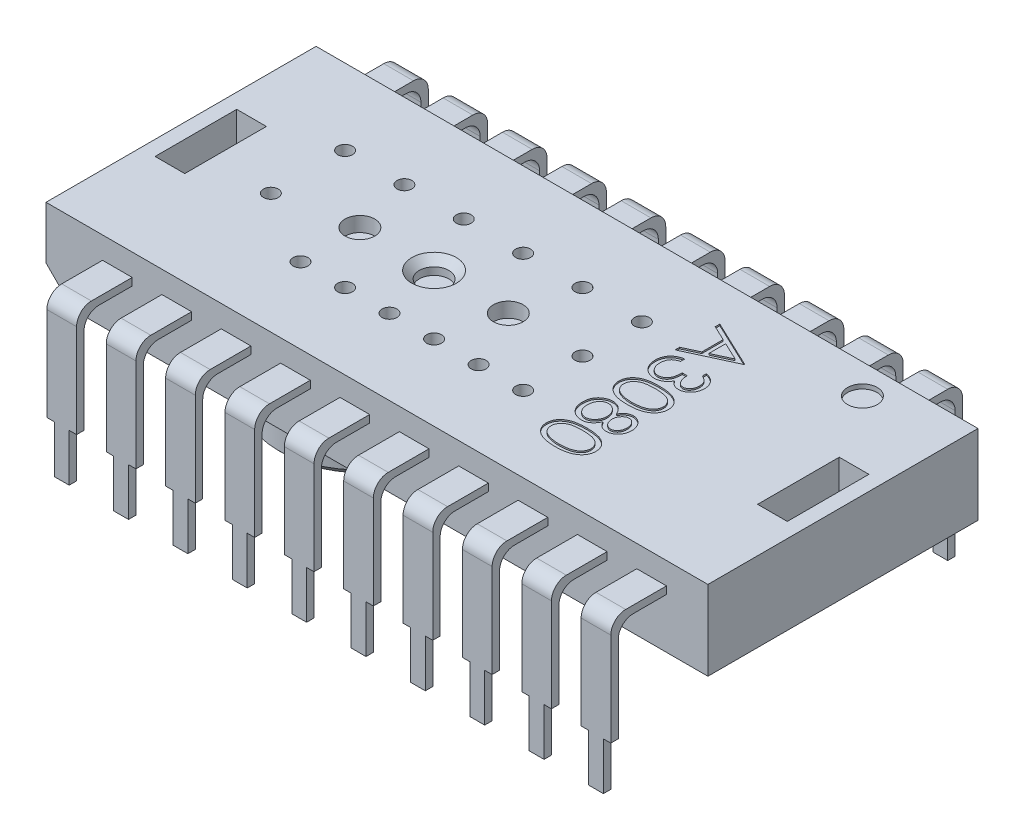
SolidWorks part; units mm, degrees
ref_plane "Front Plane" through (0, 0, 0) normal (0, 0, 1) x (1, 0, 0)
ref_plane "Top Plane" through (0, 0, 0) normal (0, 1, 0) x (1, 0, 0)
ref_plane "Right Plane" through (0, 0, 0) normal (1, 0, 0) x (0, 0, -1)
sketch "Sketch1" plane through (0, 0, 0) normal (0, 1, 0) x (1, 0, 0)
  line L1 (0, 0) -> (22.3, 0)
  line L2 (0, 0) -> (0, 9.1)
  line L3 (0, 9.1) -> (22.3, 9.1)
  line L4 (22.3, 0) -> (22.3, 9.1)
  dimension "D1" = 22.3
  dimension "D2" = 9.1
extrude "Boss-Extrude1" add sketch "Sketch1" along normal blind 3.18
sketch "Sketch2" plane through (0, 0, 0) normal (0, -1, 0) x (-1, 0, 0)
  line L0 (0, 4.55) -> (-22.3, 4.55) construction
  line L1 (0, 9.1) -> (0, 0) construction
  line L2 (-22.3, 0) -> (-22.3, 9.1) construction
  circle A0 centre (-6.025, 4.55) radius 2.8
  circle A1 centre (-6.025, 4.55) radius 0.525
  dimension "D1" = 5.6
  dimension "D3" = 1.05
  dimension "D2" = 6.025
extrude "Boss-Extrude2" add sketch "Sketch2" along normal blind 2.25 draft 1.5
chamfer "Chamfer1" distance 0.3 angle 45 1 edges at (6.025, -2.25, -7.2911)
ref_plane "Plane1" through (0, 2.19, 0) normal (0, 1, 0) x (1, 0, 0)
sketch "Sketch3" plane through (0, 2.19, 0) normal (0, 1, 0) x (1, 0, 0)
  line L0 (18.905, 9.1) -> (18.905, 10.975)
  line L1 (22.3, 9.1) -> (0, 9.1) construction
  line L2 (18.905, 10.975) -> (19.905, 10.975)
  line L3 (19.905, 10.975) -> (19.905, 9.1)
  line L4 (16.905, 9.1) -> (16.905, 10.975)
  line L5 (16.905, 10.975) -> (17.905, 10.975)
  line L6 (17.905, 10.975) -> (17.905, 9.1)
  line L7 (14.905, 9.1) -> (14.905, 10.975)
  line L8 (14.905, 10.975) -> (15.905, 10.975)
  line L9 (15.905, 10.975) -> (15.905, 9.1)
  line L10 (12.905, 9.1) -> (12.905, 10.975)
  line L11 (12.905, 10.975) -> (13.905, 10.975)
  line L12 (13.905, 10.975) -> (13.905, 9.1)
  line L13 (10.905, 9.1) -> (10.905, 10.975)
  line L14 (10.905, 10.975) -> (11.905, 10.975)
  line L15 (11.905, 10.975) -> (11.905, 9.1)
  line L16 (8.905, 9.1) -> (8.905, 10.975)
  line L17 (8.905, 10.975) -> (9.905, 10.975)
  line L18 (9.905, 10.975) -> (9.905, 9.1)
  line L19 (6.905, 9.1) -> (6.905, 10.975)
  line L20 (6.905, 10.975) -> (7.905, 10.975)
  line L21 (7.905, 10.975) -> (7.905, 9.1)
  line L22 (4.905, 9.1) -> (4.905, 10.975)
  line L23 (4.905, 10.975) -> (5.905, 10.975)
  line L24 (5.905, 10.975) -> (5.905, 9.1)
  line L25 (2.905, 9.1) -> (2.905, 10.975)
  line L26 (2.905, 10.975) -> (3.905, 10.975)
  line L27 (3.905, 10.975) -> (3.905, 9.1)
  line L28 (0.905, 9.1) -> (0.905, 10.975)
  line L29 (0.905, 10.975) -> (1.905, 10.975)
  line L30 (1.905, 10.975) -> (1.905, 9.1)
  line L31 (0, 0) -> (22.3, 0) construction
  line L32 (20.905, 0) -> (19.905, 0)
  line L33 (20.905, 0) -> (20.905, -1.875)
  line L34 (20.905, -1.875) -> (19.905, -1.875)
  line L35 (19.905, 0) -> (19.905, -1.875)
  line L36 (18.905, 0) -> (17.905, 0)
  line L37 (18.905, 0) -> (18.905, -1.875)
  line L38 (18.905, -1.875) -> (17.905, -1.875)
  line L39 (17.905, 0) -> (17.905, -1.875)
  line L40 (16.905, 0) -> (15.905, 0)
  line L41 (16.905, 0) -> (16.905, -1.875)
  line L42 (16.905, -1.875) -> (15.905, -1.875)
  line L43 (15.905, 0) -> (15.905, -1.875)
  line L44 (14.905, 0) -> (13.905, 0)
  line L45 (14.905, 0) -> (14.905, -1.875)
  line L46 (14.905, -1.875) -> (13.905, -1.875)
  line L47 (13.905, 0) -> (13.905, -1.875)
  line L48 (12.905, 0) -> (11.905, 0)
  line L49 (12.905, 0) -> (12.905, -1.875)
  line L50 (12.905, -1.875) -> (11.905, -1.875)
  line L51 (11.905, 0) -> (11.905, -1.875)
  line L52 (10.905, 0) -> (9.905, 0)
  line L53 (10.905, 0) -> (10.905, -1.875)
  line L54 (10.905, -1.875) -> (9.905, -1.875)
  line L55 (9.905, 0) -> (9.905, -1.875)
  line L56 (8.905, 0) -> (7.905, 0)
  line L57 (8.905, 0) -> (8.905, -1.875)
  line L58 (8.905, -1.875) -> (7.905, -1.875)
  line L59 (7.905, 0) -> (7.905, -1.875)
  line L60 (6.905, 0) -> (5.905, 0)
  line L61 (6.905, 0) -> (6.905, -1.875)
  line L62 (6.905, -1.875) -> (5.905, -1.875)
  line L63 (5.905, 0) -> (5.905, -1.875)
  line L64 (4.905, 0) -> (3.905, 0)
  line L65 (4.905, 0) -> (4.905, -1.875)
  line L66 (4.905, -1.875) -> (3.905, -1.875)
  line L67 (3.905, 0) -> (3.905, -1.875)
  line L68 (2.905, 0) -> (1.905, 0)
  line L69 (2.905, 0) -> (2.905, -1.875)
  line L70 (2.905, -1.875) -> (1.905, -1.875)
  line L71 (1.905, 0) -> (1.905, -1.875)
  line L72 (19.905, 9.1) -> (18.905, 9.1)
  line L73 (17.905, 9.1) -> (16.905, 9.1)
  line L74 (1.905, 9.1) -> (0.905, 9.1)
  line L75 (3.905, 9.1) -> (2.905, 9.1)
  line L76 (5.905, 9.1) -> (4.905, 9.1)
  line L77 (7.905, 9.1) -> (6.905, 9.1)
  line L78 (9.905, 9.1) -> (8.905, 9.1)
  line L79 (11.905, 9.1) -> (10.905, 9.1)
  line L80 (13.905, 9.1) -> (12.905, 9.1)
  line L81 (15.905, 9.1) -> (14.905, 9.1)
  circle A0 centre (6.025, 4.55) radius 0.525 construction
  point P6 (19.405, 10.975)
  point P51 (20.405, 0)
  dimension "D1" = 1.875
  dimension "D2" = 1
  dimension "D3" = 13.38
  dimension "D5" = 1.875
  dimension "D6" = 1
  dimension "D7" = 1
  dimension "D4" = 10
  dimension "D8" = 10
extrude "Boss-Extrude3" add sketch "Sketch3" along normal blind 0.25
sketch "Sketch5" plane through (0, 0, 1.875) normal (0, 0, 1) x (1, 0, 0)
  line L0 (2.905, 2.44) -> (1.905, 2.44) construction
  line L1 (1.905, 2.19) -> (2.905, 2.19)
  line L2 (1.905, 2.19) -> (1.905, -1.21)
  line L3 (2.155, -4.61) -> (2.655, -4.61)
  line L4 (2.905, 2.19) -> (2.905, -1.21)
  line L5 (1.905, -1.21) -> (2.155, -1.21)
  line L6 (0, 0) -> (22.3, 0) construction
  line L7 (2.405, 2.19) -> (2.405, -4.61) construction
  line L8 (2.155, -1.21) -> (2.155, -4.61)
  line L9 (2.655, -1.21) -> (2.655, -4.61)
  line L10 (2.655, -1.21) -> (2.905, -1.21)
  line L11 (3.905, 2.19) -> (4.905, 2.19)
  line L12 (3.905, 2.19) -> (3.905, -1.21)
  line L13 (4.155, -4.61) -> (4.655, -4.61)
  line L14 (4.905, 2.19) -> (4.905, -1.21)
  line L15 (3.905, -1.21) -> (4.155, -1.21)
  line L16 (4.155, -1.21) -> (4.155, -4.61)
  line L17 (4.655, -1.21) -> (4.655, -4.61)
  line L18 (4.655, -1.21) -> (4.905, -1.21)
  line L19 (4.405, 2.19) -> (4.405, -4.61) construction
  line L20 (5.905, 2.19) -> (6.905, 2.19)
  line L21 (5.905, 2.19) -> (5.905, -1.21)
  line L22 (6.155, -4.61) -> (6.655, -4.61)
  line L23 (6.905, 2.19) -> (6.905, -1.21)
  line L24 (5.905, -1.21) -> (6.155, -1.21)
  line L25 (6.155, -1.21) -> (6.155, -4.61)
  line L26 (6.655, -1.21) -> (6.655, -4.61)
  line L27 (6.655, -1.21) -> (6.905, -1.21)
  line L28 (6.405, 2.19) -> (6.405, -4.61) construction
  line L29 (7.905, 2.19) -> (8.905, 2.19)
  line L30 (7.905, 2.19) -> (7.905, -1.21)
  line L31 (8.155, -4.61) -> (8.655, -4.61)
  line L32 (8.905, 2.19) -> (8.905, -1.21)
  line L33 (7.905, -1.21) -> (8.155, -1.21)
  line L34 (8.155, -1.21) -> (8.155, -4.61)
  line L35 (8.655, -1.21) -> (8.655, -4.61)
  line L36 (8.655, -1.21) -> (8.905, -1.21)
  line L37 (8.405, 2.19) -> (8.405, -4.61) construction
  line L38 (9.905, 2.19) -> (10.905, 2.19)
  line L39 (9.905, 2.19) -> (9.905, -1.21)
  line L40 (10.155, -4.61) -> (10.655, -4.61)
  line L41 (10.905, 2.19) -> (10.905, -1.21)
  line L42 (9.905, -1.21) -> (10.155, -1.21)
  line L43 (10.155, -1.21) -> (10.155, -4.61)
  line L44 (10.655, -1.21) -> (10.655, -4.61)
  line L45 (10.655, -1.21) -> (10.905, -1.21)
  line L46 (10.405, 2.19) -> (10.405, -4.61) construction
  line L47 (11.905, 2.19) -> (12.905, 2.19)
  line L48 (11.905, 2.19) -> (11.905, -1.21)
  line L49 (12.155, -4.61) -> (12.655, -4.61)
  line L50 (12.905, 2.19) -> (12.905, -1.21)
  line L51 (11.905, -1.21) -> (12.155, -1.21)
  line L52 (12.155, -1.21) -> (12.155, -4.61)
  line L53 (12.655, -1.21) -> (12.655, -4.61)
  line L54 (12.655, -1.21) -> (12.905, -1.21)
  line L55 (12.405, 2.19) -> (12.405, -4.61) construction
  line L56 (13.905, 2.19) -> (14.905, 2.19)
  line L57 (13.905, 2.19) -> (13.905, -1.21)
  line L58 (14.155, -4.61) -> (14.655, -4.61)
  line L59 (14.905, 2.19) -> (14.905, -1.21)
  line L60 (13.905, -1.21) -> (14.155, -1.21)
  line L61 (14.155, -1.21) -> (14.155, -4.61)
  line L62 (14.655, -1.21) -> (14.655, -4.61)
  line L63 (14.655, -1.21) -> (14.905, -1.21)
  line L64 (14.405, 2.19) -> (14.405, -4.61) construction
  line L65 (15.905, 2.19) -> (16.905, 2.19)
  line L66 (15.905, 2.19) -> (15.905, -1.21)
  line L67 (16.155, -4.61) -> (16.655, -4.61)
  line L68 (16.905, 2.19) -> (16.905, -1.21)
  line L69 (15.905, -1.21) -> (16.155, -1.21)
  line L70 (16.155, -1.21) -> (16.155, -4.61)
  line L71 (16.655, -1.21) -> (16.655, -4.61)
  line L72 (16.655, -1.21) -> (16.905, -1.21)
  line L73 (16.405, 2.19) -> (16.405, -4.61) construction
  line L74 (17.905, 2.19) -> (18.905, 2.19)
  line L75 (17.905, 2.19) -> (17.905, -1.21)
  line L76 (18.155, -4.61) -> (18.655, -4.61)
  line L77 (18.905, 2.19) -> (18.905, -1.21)
  line L78 (17.905, -1.21) -> (18.155, -1.21)
  line L79 (18.155, -1.21) -> (18.155, -4.61)
  line L80 (18.655, -1.21) -> (18.655, -4.61)
  line L81 (18.655, -1.21) -> (18.905, -1.21)
  line L82 (18.405, 2.19) -> (18.405, -4.61) construction
  line L83 (19.905, 2.19) -> (20.905, 2.19)
  line L84 (19.905, 2.19) -> (19.905, -1.21)
  line L85 (20.155, -4.61) -> (20.655, -4.61)
  line L86 (20.905, 2.19) -> (20.905, -1.21)
  line L87 (19.905, -1.21) -> (20.155, -1.21)
  line L88 (20.155, -1.21) -> (20.155, -4.61)
  line L89 (20.655, -1.21) -> (20.655, -4.61)
  line L90 (20.655, -1.21) -> (20.905, -1.21)
  line L91 (20.405, 2.19) -> (20.405, -4.61) construction
  dimension "D1" = 1
  dimension "D2" = 7.05
  dimension "D3" = 1.21
  dimension "D4" = 0.25
  dimension "D5" = 0.25
  dimension "D6" = 10
extrude "Boss-Extrude4" add sketch "Sketch5" against normal blind 0.25
sketch "Sketch6" plane through (0, 0, -10.975) normal (0, 0, -1) x (-1, 0, 0)
  line L0 (-19.905, 2.19) -> (-19.905, -1.21)
  line L1 (-19.905, -1.21) -> (-19.655, -1.21)
  line L2 (-19.655, -1.21) -> (-19.655, -4.61)
  line L3 (-19.655, -4.61) -> (-19.155, -4.61)
  line L4 (-19.155, -4.61) -> (-19.155, -1.21)
  line L5 (-19.155, -1.21) -> (-18.905, -1.21)
  line L6 (-18.905, -1.21) -> (-18.905, 2.19)
  line L7 (-19.905, 2.44) -> (-18.905, 2.44) construction
  line L8 (-19.905, 2.19) -> (-18.905, 2.19)
  line L9 (-17.905, 2.19) -> (-17.905, -1.21)
  line L10 (-17.905, -1.21) -> (-17.655, -1.21)
  line L11 (-17.655, -1.21) -> (-17.655, -4.61)
  line L12 (-17.655, -4.61) -> (-17.155, -4.61)
  line L13 (-17.155, -4.61) -> (-17.155, -1.21)
  line L14 (-17.155, -1.21) -> (-16.905, -1.21)
  line L15 (-16.905, -1.21) -> (-16.905, 2.19)
  line L16 (-17.905, 2.19) -> (-16.905, 2.19)
  line L17 (-15.905, 2.19) -> (-15.905, -1.21)
  line L18 (-15.905, -1.21) -> (-15.655, -1.21)
  line L19 (-15.655, -1.21) -> (-15.655, -4.61)
  line L20 (-15.655, -4.61) -> (-15.155, -4.61)
  line L21 (-15.155, -4.61) -> (-15.155, -1.21)
  line L22 (-15.155, -1.21) -> (-14.905, -1.21)
  line L23 (-14.905, -1.21) -> (-14.905, 2.19)
  line L24 (-15.905, 2.19) -> (-14.905, 2.19)
  line L25 (-13.905, 2.19) -> (-13.905, -1.21)
  line L26 (-13.905, -1.21) -> (-13.655, -1.21)
  line L27 (-13.655, -1.21) -> (-13.655, -4.61)
  line L28 (-13.655, -4.61) -> (-13.155, -4.61)
  line L29 (-13.155, -4.61) -> (-13.155, -1.21)
  line L30 (-13.155, -1.21) -> (-12.905, -1.21)
  line L31 (-12.905, -1.21) -> (-12.905, 2.19)
  line L32 (-13.905, 2.19) -> (-12.905, 2.19)
  line L33 (-11.905, 2.19) -> (-11.905, -1.21)
  line L34 (-11.905, -1.21) -> (-11.655, -1.21)
  line L35 (-11.655, -1.21) -> (-11.655, -4.61)
  line L36 (-11.655, -4.61) -> (-11.155, -4.61)
  line L37 (-11.155, -4.61) -> (-11.155, -1.21)
  line L38 (-11.155, -1.21) -> (-10.905, -1.21)
  line L39 (-10.905, -1.21) -> (-10.905, 2.19)
  line L40 (-11.905, 2.19) -> (-10.905, 2.19)
  line L41 (-9.905, 2.19) -> (-9.905, -1.21)
  line L42 (-9.905, -1.21) -> (-9.655, -1.21)
  line L43 (-9.655, -1.21) -> (-9.655, -4.61)
  line L44 (-9.655, -4.61) -> (-9.155, -4.61)
  line L45 (-9.155, -4.61) -> (-9.155, -1.21)
  line L46 (-9.155, -1.21) -> (-8.905, -1.21)
  line L47 (-8.905, -1.21) -> (-8.905, 2.19)
  line L48 (-9.905, 2.19) -> (-8.905, 2.19)
  line L49 (-7.905, 2.19) -> (-7.905, -1.21)
  line L50 (-7.905, -1.21) -> (-7.655, -1.21)
  line L51 (-7.655, -1.21) -> (-7.655, -4.61)
  line L52 (-7.655, -4.61) -> (-7.155, -4.61)
  line L53 (-7.155, -4.61) -> (-7.155, -1.21)
  line L54 (-7.155, -1.21) -> (-6.905, -1.21)
  line L55 (-6.905, -1.21) -> (-6.905, 2.19)
  line L56 (-7.905, 2.19) -> (-6.905, 2.19)
  line L57 (-5.905, 2.19) -> (-5.905, -1.21)
  line L58 (-5.905, -1.21) -> (-5.655, -1.21)
  line L59 (-5.655, -1.21) -> (-5.655, -4.61)
  line L60 (-5.655, -4.61) -> (-5.155, -4.61)
  line L61 (-5.155, -4.61) -> (-5.155, -1.21)
  line L62 (-5.155, -1.21) -> (-4.905, -1.21)
  line L63 (-4.905, -1.21) -> (-4.905, 2.19)
  line L64 (-5.905, 2.19) -> (-4.905, 2.19)
  line L65 (-3.905, 2.19) -> (-3.905, -1.21)
  line L66 (-3.905, -1.21) -> (-3.655, -1.21)
  line L67 (-3.655, -1.21) -> (-3.655, -4.61)
  line L68 (-3.655, -4.61) -> (-3.155, -4.61)
  line L69 (-3.155, -4.61) -> (-3.155, -1.21)
  line L70 (-3.155, -1.21) -> (-2.905, -1.21)
  line L71 (-2.905, -1.21) -> (-2.905, 2.19)
  line L72 (-3.905, 2.19) -> (-2.905, 2.19)
  line L73 (-1.905, 2.19) -> (-1.905, -1.21)
  line L74 (-1.905, -1.21) -> (-1.655, -1.21)
  line L75 (-1.655, -1.21) -> (-1.655, -4.61)
  line L76 (-1.655, -4.61) -> (-1.155, -4.61)
  line L77 (-1.155, -4.61) -> (-1.155, -1.21)
  line L78 (-1.155, -1.21) -> (-0.905, -1.21)
  line L79 (-0.905, -1.21) -> (-0.905, 2.19)
  line L80 (-1.905, 2.19) -> (-0.905, 2.19)
  dimension "D1" = 3.4
  dimension "D2" = 3.4
  dimension "D3" = 7.05
  dimension "D4" = 0.25
  dimension "D5" = 0.25
  dimension "D6" = 10
extrude "Boss-Extrude5" add sketch "Sketch6" against normal blind 0.25
fillet "Fillet1" radius 0.5 40 edges at (19.405, 2.19, -10.725) (17.405, 2.19, -10.725) (15.405, 2.19, -10.725) (13.405, 2.19, -10.725) (11.405, 2.19, -10.725) (9.405, 2.19, -10.725) (7.405, 2.19, -10.725) (5.405, 2.19, -10.725) (3.405, 2.19, -10.725) (1.405, 2.19, -10.725) (18.405, 2.19, 1.625) (16.405, 2.19, 1.625) (14.405, 2.19, 1.625) (12.405, 2.19, 1.625) (10.405, 2.19, 1.625) (8.405, 2.19, 1.625) (6.405, 2.19, 1.625) (4.405, 2.19, 1.625) (2.405, 2.19, 1.625) (5.405, 2.44, -10.975) (3.405, 2.44, -10.975) (1.405, 2.44, -10.975) (7.405, 2.44, -10.975) (9.405, 2.44, -10.975) (11.405, 2.44, -10.975) (13.405, 2.44, -10.975) (15.405, 2.44, -10.975) (17.405, 2.44, -10.975) (19.405, 2.44, -10.975) (18.405, 2.44, 1.875) (16.405, 2.44, 1.875) (14.405, 2.44, 1.875) (12.405, 2.44, 1.875) (10.405, 2.44, 1.875) (8.405, 2.44, 1.875) (6.405, 2.44, 1.875) (4.405, 2.44, 1.875) (2.405, 2.44, 1.875) (20.405, 2.19, 1.625) (20.405, 2.44, 1.875)
sketch "Sketch7" plane through (0, 0, -10.975) normal (0, 0, 1) x (1, 0, 0)
  line L0 (1.53, -4.61) -> (1.655, -3.61)
  line L1 (1.655, -4.61) -> (1.155, -4.61) construction
  line L2 (1.655, -1.21) -> (1.655, -4.61) construction
  line L3 (1.28, -4.61) -> (1.155, -3.61)
  line L4 (1.155, -4.61) -> (1.155, -1.21) construction
  line L5 (1.155, -3.61) -> (1.155, -4.61)
  line L6 (1.155, -4.61) -> (1.28, -4.61)
  line L7 (1.53, -4.61) -> (1.655, -4.61)
  line L8 (1.655, -4.61) -> (1.655, -3.61)
  line L9 (2.53, -4.61) -> (2.655, -3.61)
  line L10 (2.28, -4.61) -> (2.155, -3.61)
  line L11 (2.155, -3.61) -> (2.155, -4.61)
  line L12 (2.155, -4.61) -> (2.28, -4.61)
  line L13 (2.53, -4.61) -> (2.655, -4.61)
  line L14 (2.655, -4.61) -> (2.655, -3.61)
  line L15 (3.53, -4.61) -> (3.655, -3.61)
  line L16 (3.28, -4.61) -> (3.155, -3.61)
  line L17 (3.155, -3.61) -> (3.155, -4.61)
  line L18 (3.155, -4.61) -> (3.28, -4.61)
  line L19 (3.53, -4.61) -> (3.655, -4.61)
  line L20 (3.655, -4.61) -> (3.655, -3.61)
  line L21 (4.53, -4.61) -> (4.655, -3.61)
  line L22 (4.28, -4.61) -> (4.155, -3.61)
  line L23 (4.155, -3.61) -> (4.155, -4.61)
  line L24 (4.155, -4.61) -> (4.28, -4.61)
  line L25 (4.53, -4.61) -> (4.655, -4.61)
  line L26 (4.655, -4.61) -> (4.655, -3.61)
  line L27 (5.53, -4.61) -> (5.655, -3.61)
  line L28 (5.28, -4.61) -> (5.155, -3.61)
  line L29 (5.155, -3.61) -> (5.155, -4.61)
  line L30 (5.155, -4.61) -> (5.28, -4.61)
  line L31 (5.53, -4.61) -> (5.655, -4.61)
  line L32 (5.655, -4.61) -> (5.655, -3.61)
  line L33 (6.53, -4.61) -> (6.655, -3.61)
  line L34 (6.28, -4.61) -> (6.155, -3.61)
  line L35 (6.155, -3.61) -> (6.155, -4.61)
  line L36 (6.155, -4.61) -> (6.28, -4.61)
  line L37 (6.53, -4.61) -> (6.655, -4.61)
  line L38 (6.655, -4.61) -> (6.655, -3.61)
  line L39 (7.53, -4.61) -> (7.655, -3.61)
  line L40 (7.28, -4.61) -> (7.155, -3.61)
  line L41 (7.155, -3.61) -> (7.155, -4.61)
  line L42 (7.155, -4.61) -> (7.28, -4.61)
  line L43 (7.53, -4.61) -> (7.655, -4.61)
  line L44 (7.655, -4.61) -> (7.655, -3.61)
  line L45 (8.53, -4.61) -> (8.655, -3.61)
  line L46 (8.28, -4.61) -> (8.155, -3.61)
  line L47 (8.155, -3.61) -> (8.155, -4.61)
  line L48 (8.155, -4.61) -> (8.28, -4.61)
  line L49 (8.53, -4.61) -> (8.655, -4.61)
  line L50 (8.655, -4.61) -> (8.655, -3.61)
  line L51 (9.53, -4.61) -> (9.655, -3.61)
  line L52 (9.28, -4.61) -> (9.155, -3.61)
  line L53 (9.155, -3.61) -> (9.155, -4.61)
  line L54 (9.155, -4.61) -> (9.28, -4.61)
  line L55 (9.53, -4.61) -> (9.655, -4.61)
  line L56 (9.655, -4.61) -> (9.655, -3.61)
  line L57 (10.53, -4.61) -> (10.655, -3.61)
  line L58 (10.28, -4.61) -> (10.155, -3.61)
  line L59 (10.155, -3.61) -> (10.155, -4.61)
  line L60 (10.155, -4.61) -> (10.28, -4.61)
  line L61 (10.53, -4.61) -> (10.655, -4.61)
  line L62 (10.655, -4.61) -> (10.655, -3.61)
  line L63 (11.53, -4.61) -> (11.655, -3.61)
  line L64 (11.28, -4.61) -> (11.155, -3.61)
  line L65 (11.155, -3.61) -> (11.155, -4.61)
  line L66 (11.155, -4.61) -> (11.28, -4.61)
  line L67 (11.53, -4.61) -> (11.655, -4.61)
  line L68 (11.655, -4.61) -> (11.655, -3.61)
  line L69 (12.53, -4.61) -> (12.655, -3.61)
  line L70 (12.28, -4.61) -> (12.155, -3.61)
  line L71 (12.155, -3.61) -> (12.155, -4.61)
  line L72 (12.155, -4.61) -> (12.28, -4.61)
  line L73 (12.53, -4.61) -> (12.655, -4.61)
  line L74 (12.655, -4.61) -> (12.655, -3.61)
  line L75 (13.53, -4.61) -> (13.655, -3.61)
  line L76 (13.28, -4.61) -> (13.155, -3.61)
  line L77 (13.155, -3.61) -> (13.155, -4.61)
  line L78 (13.155, -4.61) -> (13.28, -4.61)
  line L79 (13.53, -4.61) -> (13.655, -4.61)
  line L80 (13.655, -4.61) -> (13.655, -3.61)
  line L81 (14.53, -4.61) -> (14.655, -3.61)
  line L82 (14.28, -4.61) -> (14.155, -3.61)
  line L83 (14.155, -3.61) -> (14.155, -4.61)
  line L84 (14.155, -4.61) -> (14.28, -4.61)
  line L85 (14.53, -4.61) -> (14.655, -4.61)
  line L86 (14.655, -4.61) -> (14.655, -3.61)
  line L87 (15.53, -4.61) -> (15.655, -3.61)
  line L88 (15.28, -4.61) -> (15.155, -3.61)
  line L89 (15.155, -3.61) -> (15.155, -4.61)
  line L90 (15.155, -4.61) -> (15.28, -4.61)
  line L91 (15.53, -4.61) -> (15.655, -4.61)
  line L92 (15.655, -4.61) -> (15.655, -3.61)
  line L93 (16.53, -4.61) -> (16.655, -3.61)
  line L94 (16.28, -4.61) -> (16.155, -3.61)
  line L95 (16.155, -3.61) -> (16.155, -4.61)
  line L96 (16.155, -4.61) -> (16.28, -4.61)
  line L97 (16.53, -4.61) -> (16.655, -4.61)
  line L98 (16.655, -4.61) -> (16.655, -3.61)
  line L99 (17.53, -4.61) -> (17.655, -3.61)
  line L100 (17.28, -4.61) -> (17.155, -3.61)
  line L101 (17.155, -3.61) -> (17.155, -4.61)
  line L102 (17.155, -4.61) -> (17.28, -4.61)
  line L103 (17.53, -4.61) -> (17.655, -4.61)
  line L104 (17.655, -4.61) -> (17.655, -3.61)
  line L105 (18.53, -4.61) -> (18.655, -3.61)
  line L106 (18.28, -4.61) -> (18.155, -3.61)
  line L107 (18.155, -3.61) -> (18.155, -4.61)
  line L108 (18.155, -4.61) -> (18.28, -4.61)
  line L109 (18.53, -4.61) -> (18.655, -4.61)
  line L110 (18.655, -4.61) -> (18.655, -3.61)
  line L111 (19.53, -4.61) -> (19.655, -3.61)
  line L112 (19.28, -4.61) -> (19.155, -3.61)
  line L113 (19.155, -3.61) -> (19.155, -4.61)
  line L114 (19.155, -4.61) -> (19.28, -4.61)
  line L115 (19.53, -4.61) -> (19.655, -4.61)
  line L116 (19.655, -4.61) -> (19.655, -3.61)
  line L117 (20.53, -4.61) -> (20.655, -3.61)
  line L118 (20.28, -4.61) -> (20.155, -3.61)
  line L119 (20.155, -3.61) -> (20.155, -4.61)
  line L120 (20.155, -4.61) -> (20.28, -4.61)
  line L121 (20.53, -4.61) -> (20.655, -4.61)
  line L122 (20.655, -4.61) -> (20.655, -3.61)
  dimension "D1" = 0.125
  dimension "D2" = 0.125
  dimension "D3" = 1
  dimension "D4" = 1
  dimension "D5" = 20
extrude "Cut-Extrude1" cut sketch "Sketch7" along normal through all
sketch "Sketch8" plane through (0, 0, 0) normal (0, -1, 0) x (-1, 0, 0)
  line L0 (0, 4.55) -> (-22.3, 4.55) construction
  line L1 (0, 0) -> (-22.3, 0)
  line L2 (0, 0) -> (0, 9.1)
  line L3 (0, 9.1) -> (-22.3, 9.1)
  line L4 (-22.3, 0) -> (-22.3, 9.1)
  line L5 (-1.41, 0.91) -> (-20.89, 0.91)
  line L6 (-1.41, 0.91) -> (-1.41, 8.19)
  line L7 (-1.41, 8.19) -> (-20.89, 8.19)
  line L8 (-20.89, 0.91) -> (-20.89, 8.19)
  dimension "D1" = 7.28
  dimension "D2" = 3.64
  dimension "D3" = 1.41
  dimension "D4" = 0.91
  dimension "D5" = 1.41
extrude "Cut-Extrude2" cut sketch "Sketch8" against normal blind 0.5
chamfer "Chamfer2" distance 0.91 angle 45 1 edges at (0, 0.5, -4.55)
sketch "Sketch9" plane through (0, 0, 0) normal (0, -1, 0) x (-1, 0, 0)
  line L0 (-1.41, 4.55) -> (-20.89, 4.55) construction
  line L1 (-1.41, 0.91) -> (-1.41, 8.19) construction
  line L2 (-20.89, 8.19) -> (-20.89, 0.91) construction
  line L5 (-1.41, 3.05) -> (-1.41, 6.05)
  line L7 (-2.41, 4.05) -> (-2.41, 5.05)
  arc A0 (-1.41, 3.05) -> (-2.41, 4.05) centre (-1.41, 4.05) cw
  arc A1 (-1.41, 6.05) -> (-2.41, 5.05) centre (-1.41, 5.05) ccw
  dimension "D4" = 1
  dimension "D3" = 0.5
  dimension "D1" = 1
  dimension "D2" = 3
extrude "Cut-Extrude3" cut sketch "Sketch9" against normal up to surface (0.5 mm away) up to face at (11.15, 0.5, -4.55)
sketch "Sketch11" plane through (0, 3.18, 0) normal (0, 1, 0) x (1, 0, 0)
  line L0 (19.405, 9.1) -> (19.405, 0) construction
  line L1 (18.905, 9.1) -> (19.905, 9.1) construction
  line L2 (0, 0) -> (22.3, 0) construction
  line L3 (22.3, 9.1) -> (0, 9.1) construction
  circle A0 centre (19.405, 8.1) radius 0.5
  dimension "D1" = 1
  dimension "D2" = 1
extrude "Cut-Extrude5" cut sketch "Sketch11" against normal blind 0.15
sketch "Sketch13" plane through (0, 3.18, 0) normal (0, 1, 0) x (1, 0, 0)
  line L0 (0, 4.55) -> (22.3, 4.55) construction
  line L1 (3.525, 6.55) -> (13.525, 6.55) construction
  line L2 (3.525, 6.55) -> (3.525, 2.55) construction
  line L3 (3.525, 2.55) -> (13.525, 2.55) construction
  line L4 (13.525, 6.55) -> (13.525, 2.55) construction
  line L5 (0, 9.1) -> (0, 0) construction
  line L6 (22.3, 0) -> (22.3, 9.1) construction
  circle A0 centre (6.025, 4.55) radius 0.5
  circle A1 centre (8.525, 4.55) radius 0.5
  circle A2 centre (11.025, 4.55) radius 0.5
  circle A3 centre (3.525, 6.55) radius 0.25
  circle A4 centre (5.525, 6.55) radius 0.25
  circle A5 centre (7.525, 6.55) radius 0.25
  circle A6 centre (9.525, 6.55) radius 0.25
  circle A7 centre (11.525, 6.55) radius 0.25
  circle A8 centre (13.525, 6.55) radius 0.25
  circle A9 centre (13.525, 4.55) radius 0.25
  circle A10 centre (13.525, 2.55) radius 0.25
  circle A11 centre (12.025, 2.55) radius 0.25
  circle A12 centre (10.525, 2.55) radius 0.25
  circle A13 centre (9.025, 2.55) radius 0.25
  circle A14 centre (7.525, 2.55) radius 0.25
  circle A15 centre (6.025, 2.55) radius 0.25
  circle A16 centre (3.525, 4.05) radius 0.25
  dimension "D1" = 1
  dimension "D5" = 2
  dimension "D6" = 5
  dimension "D7" = 5
  dimension "D8" = 0.5
  dimension "D2" = 6.025
  dimension "D4" = 2
  dimension "D3" = 3
  dimension "D9" = 6
  dimension "D10" = 3
  dimension "D11" = 6
  dimension "D12" = 2
extrude "Cut-Extrude6" cut sketch "Sketch13" against normal blind 0.5
chamfer "Chamfer3" distance 0.25 angle 45 1 edges at (8.525, 3.18, -4.05)
sketch "Sketch14" plane through (0, 3.18, 0) normal (0, 1, 0) x (1, 0, 0)
  line L0 (0, 4.55) -> (22.3, 4.55) construction
  line L1 (0, 9.1) -> (0, 0) construction
  line L2 (22.3, 0) -> (22.3, 9.1) construction
  line L3 (11.15, 9.1) -> (11.15, 0) construction
  line L4 (0.5, 5.925) -> (1.5, 5.925)
  line L5 (0.5, 5.925) -> (0.5, 3.175)
  line L6 (0.5, 3.175) -> (1.5, 3.175)
  line L7 (1.5, 5.925) -> (1.5, 3.175)
  line L8 (22.3, 9.1) -> (0, 9.1) construction
  line L9 (0, 0) -> (22.3, 0) construction
  line L10 (20.8, 5.925) -> (20.8, 3.175)
  line L11 (21.8, 3.175) -> (20.8, 3.175)
  line L12 (21.8, 5.925) -> (21.8, 3.175)
  line L13 (21.8, 5.925) -> (20.8, 5.925)
  dimension "D1" = 2.75
  dimension "D2" = 1
  dimension "D3" = 0.5
  dimension "D4" = 1.375
extrude "Cut-Extrude7" cut sketch "Sketch14" against normal blind 1
sketch "Sketch15" plane through (0, 3.18, 0) normal (0, 1, 0) x (1, 0, 0)
  line L0 (14.905, 9.1) -> (14.905, 0) construction
  line L1 (0, 0) -> (22.3, 0) construction
  text T0 "  A3080" font "Century Gothic" height in points 6
extrude "Cut-Extrude8" cut sketch "Sketch15" against normal blind 0.05
sketch "Sketch16" plane through (0, 0, 1.875) normal (0, 0, 1) x (1, 0, 0)
  line L0 (1.905, -1.21) -> (2.155, -1.21) construction
  line L1 (1.155, -2.81) -> (20.655, -2.81)
  line L2 (1.155, -2.81) -> (1.155, -4.61)
  line L3 (1.155, -4.61) -> (20.655, -4.61)
  line L4 (20.655, -2.81) -> (20.655, -4.61)
  line L5 (1.155, -3.61) -> (1.155, -1.21) construction
  line L6 (20.655, -3.61) -> (20.655, -1.21) construction
  point P6 (2.03, -1.21)
  dimension "D1" = 1.6
extrude "Cut-Extrude9" cut sketch "Sketch16" against normal through all
